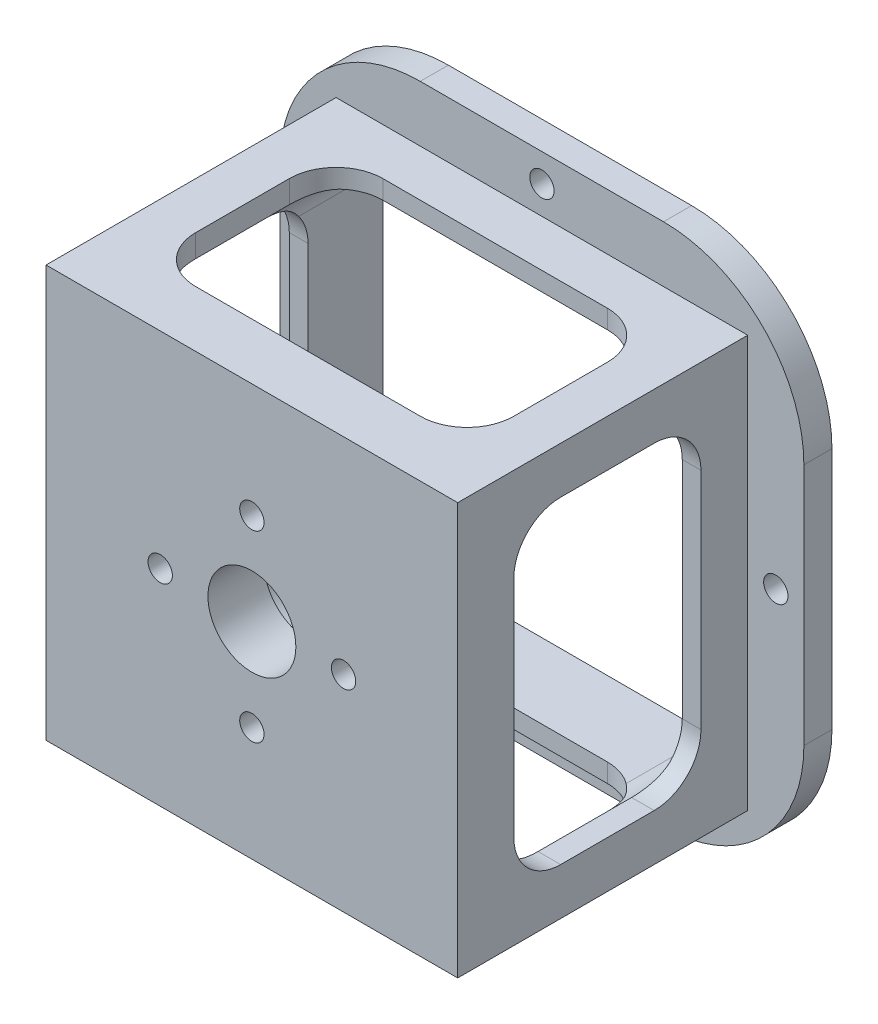
SolidWorks part; units mm, degrees
ref_plane "Front Plane" through (0, 0, 0) normal (0, 0, 1) x (1, 0, 0)
ref_plane "Top Plane" through (0, 0, 0) normal (0, 1, 0) x (1, 0, 0)
ref_plane "Right Plane" through (0, 0, 0) normal (1, 0, 0) x (0, 0, -1)
sketch "Sketch1" plane through (0, 0, 0) normal (0, 0, 1) x (1, 0, 0)
  line L0 (0, 0) -> (0, 71.12)
  line L1 (0, 71.12) -> (71.12, 71.12)
  line L2 (71.12, 71.12) -> (71.12, 0)
  line L3 (71.12, 0) -> (0, 0)
  dimension "D1" = 71.12
extrude "Boss-Extrude1" add sketch "Sketch1" along normal blind 43.18
sketch "Sketch2" plane through (0, 0, 43.18) normal (0, 0, 1) x (1, 0, 0)
  line L0 (71.12, 71.12) -> (0, 71.12) construction
  line L1 (63.5, 63.5) -> (7.62, 63.5)
  line L2 (63.5, 63.5) -> (63.5, 7.62)
  line L3 (63.5, 7.62) -> (7.62, 7.62)
  line L4 (7.62, 63.5) -> (7.62, 7.62)
  line L5 (0, 71.12) -> (0, 0) construction
  line L7 (0, 0) -> (71.12, 0)
  line L8 (0, 0) -> (0, 71.12)
  line L9 (0, 71.12) -> (71.12, 71.12)
  line L10 (71.12, 0) -> (71.12, 71.12)
  dimension "D1" = 55.88
  dimension "D2" = 7.62
  dimension "D3" = 7.62
extrude "Cut-Extrude1" cut sketch "Sketch2" against normal blind 39.37
sketch "Sketch4" plane through (0, 0, 0) normal (0, 0, -1) x (-1, 0, 0)
  line L0 (-71.12, 0) -> (-71.12, 71.12) construction
  line L1 (-60.96, 10.16) -> (-10.16, 10.16)
  line L2 (-60.96, 10.16) -> (-60.96, 60.96)
  line L3 (-60.96, 60.96) -> (-10.16, 60.96)
  line L4 (-10.16, 10.16) -> (-10.16, 60.96)
  line L5 (-71.12, 71.12) -> (0, 71.12) construction
  dimension "D1" = 50.8
  dimension "D2" = 10.16
  dimension "D3" = 10.16
extrude "Cut-Extrude2" cut sketch "Sketch4" against normal blind 35.56 contours L3 L4 L1 L2
sketch "Sketch5" plane through (0, 0, 43.18) normal (0, 0, 1) x (1, 0, 0)
  line L0 (35.56, 48.006) -> (35.56, 23.114) construction
  line L1 (23.114, 35.56) -> (48.006, 35.56) construction
  circle A0 centre (35.56, 48.006) radius 1.651
  circle A1 centre (48.006, 35.56) radius 1.651
  circle A2 centre (35.56, 23.114) radius 1.651
  circle A3 centre (23.114, 35.56) radius 1.651
  circle A4 centre (35.56, 35.56) radius 5.969
  point P4 (35.56, 35.56)
  dimension "D5" = 3.302
  dimension "D6" = 11.938
  dimension "D1" = 24.892
  dimension "D2" = 24.892
  dimension "D3" = 35.56
  dimension "D4" = 35.56
extrude "Cut-Extrude3" cut sketch "Sketch5" against normal up to next
sketch "Sketch6" plane through (0, 0, 0) normal (0, 0, -1) x (-1, 0, 0)
  line L0 (-67.31, 35.56) -> (-3.81, 35.56) construction
  line L1 (-35.56, 67.31) -> (-35.56, 3.81) construction
  circle A0 centre (-35.56, 67.31) radius 1.651
  circle A1 centre (-3.81, 35.56) radius 1.651
  circle A2 centre (-35.56, 3.81) radius 1.651
  circle A3 centre (-67.31, 35.56) radius 1.651
  point P4 (-35.56, 35.56)
  dimension "D5" = 3.302
  dimension "D3" = 35.56
  dimension "D4" = 35.56
  dimension "D1" = 63.5
  dimension "D2" = 63.5
extrude "Cut-Extrude4" cut sketch "Sketch6" against normal up to next
fillet "Fillet1" radius 6.35 4 edges at (60.96, 60.96, 17.78) (60.96, 10.16, 17.78) (10.16, 10.16, 17.78) (10.16, 60.96, 17.78)
sketch "Sketch7" plane through (7.62, 0, 0) normal (-1, 0, 0) x (0, 0, 1)
  line L0 (10.16, 20.32) -> (10.16, 50.8)
  line L1 (16.51, 57.15) -> (29.21, 57.15)
  line L2 (35.56, 50.8) -> (35.56, 20.32)
  line L3 (29.21, 13.97) -> (16.51, 13.97)
  line L4 (3.81, 63.5) -> (43.18, 63.5) construction
  line L5 (43.18, 63.5) -> (43.18, 7.62) construction
  line L6 (3.81, 7.62) -> (43.18, 7.62) construction
  line L7 (3.81, 71.12) -> (3.81, 0) construction
  arc A0 (10.16, 50.8) -> (16.51, 57.15) centre (16.51, 50.8) cw
  arc A1 (29.21, 57.15) -> (35.56, 50.8) centre (29.21, 50.8) cw
  arc A2 (29.21, 13.97) -> (35.56, 20.32) centre (29.21, 20.32) ccw
  arc A3 (10.16, 20.32) -> (16.51, 13.97) centre (16.51, 20.32) ccw
  dimension "D5" = 6.35
  dimension "D1" = 6.35
  dimension "D2" = 7.62
  dimension "D3" = 6.35
  dimension "D4" = 6.35
extrude "Cut-Extrude5" cut sketch "Sketch7" against normal up to next
pattern_circular "CirPattern1" count 4 over 360 about axis through (35.56, 35.56, 0) along (0, 0, 1) of "Cut-Extrude5"
fillet "Fillet3" radius 19.05 4 edges at (0, 0, 1.905) (0, 71.12, 1.905) (71.12, 71.12, 1.905) (71.12, 0, 1.905)
sketch "Sketch8" plane through (0, 0, 35.56) normal (0, 0, -1) x (-1, 0, 0)
  circle A0 centre (-35.56, 48.006) radius 3.175
  circle A1 centre (-23.114, 35.56) radius 3.175
  circle A2 centre (-35.56, 23.114) radius 3.175
  circle A3 centre (-48.006, 35.56) radius 3.175
  dimension "D1" = 6.35
extrude "Cut-Extrude6" cut sketch "Sketch8" against normal blind 3.81
equation "\"D1@Sketch1\"=2.2+0.6"
equation "\"D3@Sketch5\"=\"D1@Sketch1\"/2"
equation "\"D4@Sketch5\"=\"D3@Sketch5\""
equation "\"D3@Sketch6\"=\"D1@Sketch1\"/2"
equation "\"D4@Sketch6\"=\"D3@Sketch6\""
equation "\"D3@Sketch7\"=\"D1@Sketch7\""
equation "\"D4@Sketch7\"=\"D1@Sketch7\""
